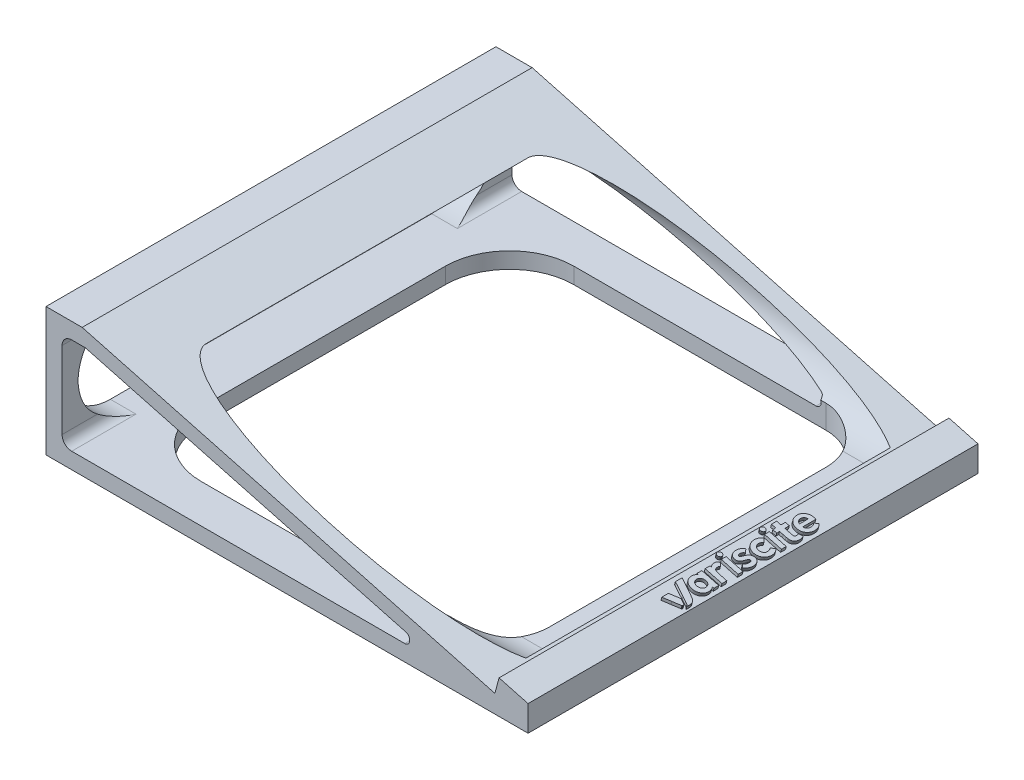
SolidWorks part; units mm, degrees
material "ABS"
ref_plane "Ebene vorne" through (0, 0, 0) normal (1, 0, 0) x (0, 1, 0)
ref_plane "Ebene oben" through (0, 0, 0) normal (0, 0, 1) x (0, 1, 0)
ref_plane "Ebene rechts" through (0, 0, 0) normal (0, 1, 0) x (-1, 0, 0)
sketch "Basis" plane through (0, 0, 0) normal (0, 0, 1) x (0, 1, 0)
  line L0 (0, 0) -> (0, 150)
  line L1 (0, 0) -> (8, 0)
  line L2 (8, 0) -> (10.4201, 9.032)
  line L3 (0, 150) -> (40, 150)
  line L4 (40, 150) -> (40, 138.7441)
  line L5 (40, 138.7441) -> (5.5905, 10.3261)
  line L6 (5.5905, 10.3261) -> (10.4201, 9.032)
  dimension "D1" = 15
  dimension "D2" = 90
  dimension "D3" = 8
  dimension "D4" = 150
  dimension "D5" = 15
  dimension "D6" = 40
  dimension "D8" = 5
extrude "Aufsatz-Linear austragen1" add sketch "Basis" along normal blind 140
sketch "Schnitt Boden" plane through (0.3591, 0, 0) normal (0, 1, 0) x (-1, 0, 0)
  line L0 (139.1032, 140) -> (139.1032, 0) construction
  line L4 (35.6851, 128) -> (114.1032, 128)
  line L6 (20.6851, 113) -> (20.6851, 27)
  line L7 (35.6851, 12) -> (114.1032, 12)
  line L8 (134.1032, 108) -> (134.1032, 32)
  line L9 (10.6851, 140) -> (139.1032, 140) construction
  line L10 (10.6851, 0) -> (139.1032, 0) construction
  line L11 (10.6851, 140) -> (10.6851, 0) construction
  arc A2 (35.6851, 128) -> (20.6851, 113) centre (35.6851, 113) ccw
  arc A3 (20.6851, 27) -> (35.6851, 12) centre (35.6851, 27) ccw
  arc A4 (134.1032, 32) -> (114.1032, 12) centre (114.1032, 32) cw
  arc A5 (134.1032, 108) -> (114.1032, 128) centre (114.1032, 108) ccw
  point P20 (10.6851, 70)
  dimension "D1" = 15
  dimension "D3" = 12
  dimension "D6" = 20
  dimension "D2" = 5
  dimension "D4" = 12
  dimension "D5" = 10
sketch "Schnitt Hinten" plane through (-150, 0, 0) normal (-1, 0, 0) x (0, -1, 0)
  line L0 (-20, 120) -> (-20, 20) construction
  line L1 (-5, 120) -> (-5, 20)
  line L2 (-35, 120) -> (-35, 20)
  line L3 (-40, 0) -> (0, 0) construction
  line L4 (0, 140) -> (0, 0) construction
  arc A0 (-5, 120) -> (-35, 120) centre (-20, 120) ccw
  arc A1 (-35, 20) -> (-5, 20) centre (-20, 20) ccw
  point P2 (-20, 70)
  dimension "D1" = 70
  dimension "D2" = 20
extrude "Schnitt Hinten austragen" cut sketch "Schnitt Hinten" against normal blind 136
extrude "Schnitt Boden austragen" cut sketch "Schnitt Boden" along normal blind 10
sketch "Schnitt Seite" plane through (0, 0, 140) normal (0, 0, 1) x (1, 0, 0)
  line L0 (-142, 35) -> (-137.7635, 35)
  line L1 (-137.7635, 35) -> (-37.9725, 8.2611)
  line L2 (-36.8607, 6.8122) -> (-36.8607, 6.5)
  line L3 (-38.3607, 5) -> (-142, 5)
  line L4 (-145, 8) -> (-145, 32)
  line L5 (-150, 40) -> (-150, 0) construction
  line L6 (-150, 0) -> (0, 0) construction
  line L7 (-10.3261, 5.5905) -> (-138.7441, 40) construction
  arc A0 (-145, 32) -> (-142, 35) centre (-142, 32) cw
  arc A1 (-142, 5) -> (-145, 8) centre (-142, 8) cw
  arc A2 (-38.3607, 5) -> (-36.8607, 6.5) centre (-38.3607, 6.5) ccw
  arc A3 (-36.8607, 6.8122) -> (-37.9725, 8.2611) centre (-38.3607, 6.8122) ccw
  dimension "D5" = 3
  dimension "D6" = 3
  dimension "D7" = 1.5
  dimension "D1" = 5
  dimension "D2" = 5
  dimension "D3" = 0
  dimension "D4" = 5
extrude "Schnitt Seite austragen" cut sketch "Schnitt Seite" against normal blind 140
sketch "Skizze Logo" plane through (2, 7.4641, 0) normal (0.2588, 0.9659, 0) x (-0.9659, 0.2588, 0)
  line L0 (8.7653, 83.336) -> (8.7223, 83.5503)
  line L1 (8.7223, 83.5503) -> (8.6617, 83.7574)
  line L2 (8.6617, 83.7574) -> (8.5841, 83.9565)
  line L3 (8.5841, 83.9565) -> (8.4904, 84.1471)
  line L4 (8.4904, 84.1471) -> (8.3812, 84.3284)
  line L5 (8.3812, 84.3284) -> (8.2572, 84.4998)
  line L6 (8.2572, 84.4998) -> (8.1193, 84.6607)
  line L7 (8.1193, 84.6607) -> (7.968, 84.8103)
  line L8 (7.968, 84.8103) -> (7.8042, 84.948)
  line L9 (7.8042, 84.948) -> (7.6286, 85.0731)
  line L10 (7.6286, 85.0731) -> (7.4418, 85.1851)
  line L11 (7.4418, 85.1851) -> (7.2447, 85.2831)
  line L12 (7.2447, 85.2831) -> (7.0379, 85.3666)
  line L13 (7.0379, 85.3666) -> (6.8221, 85.4349)
  line L14 (6.8221, 85.4349) -> (6.5982, 85.4873)
  line L15 (6.5982, 85.4873) -> (6.3668, 85.5232)
  line L16 (6.3668, 85.5232) -> (6.1055, 85.5395)
  line L17 (6.1055, 85.5395) -> (5.8095, 85.5358)
  line L18 (5.8095, 85.5358) -> (5.5207, 85.5139)
  line L19 (5.5207, 85.5139) -> (5.2806, 85.4757)
  line L20 (5.2806, 85.4757) -> (5.0781, 85.4227)
  line L21 (5.0781, 85.4227) -> (4.8833, 85.3574)
  line L22 (4.8833, 85.3574) -> (4.6967, 85.2803)
  line L23 (4.6967, 85.2803) -> (4.5186, 85.1917)
  line L24 (4.5186, 85.1917) -> (4.3495, 85.0921)
  line L25 (4.3495, 85.0921) -> (4.1898, 84.9818)
  line L26 (4.1898, 84.9818) -> (4.0398, 84.8613)
  line L27 (4.0398, 84.8613) -> (3.9, 84.731)
  line L28 (3.9, 84.731) -> (3.7708, 84.5913)
  line L29 (3.7708, 84.5913) -> (3.6526, 84.4425)
  line L30 (3.6526, 84.4425) -> (3.5458, 84.2852)
  line L31 (3.5458, 84.2852) -> (3.4507, 84.1196)
  line L32 (3.4507, 84.1196) -> (3.3679, 83.9462)
  line L33 (3.3679, 83.9462) -> (3.2976, 83.7654)
  line L34 (3.2976, 83.7654) -> (3.2404, 83.5777)
  line L35 (3.2404, 83.5777) -> (3.1965, 83.3833)
  line L36 (3.1965, 83.3833) -> (3.1685, 83.1466)
  line L37 (3.1685, 83.1466) -> (3.1596, 82.8688)
  line L38 (3.1596, 82.8688) -> (3.1699, 82.5946)
  line L39 (3.1699, 82.5946) -> (3.1992, 82.3684)
  line L40 (3.1992, 82.3684) -> (3.274, 82.0965)
  line L41 (3.274, 82.0965) -> (3.3828, 81.8376)
  line L42 (3.3828, 81.8376) -> (3.5252, 81.5928)
  line L43 (3.5252, 81.5928) -> (3.7004, 81.3632)
  line L44 (3.7004, 81.3632) -> (3.7878, 81.262)
  line L45 (3.7878, 81.262) -> (3.523, 81.262)
  line L46 (3.523, 81.262) -> (3.2582, 81.262)
  line L47 (3.2582, 81.262) -> (3.2582, 80.5244)
  line L48 (3.2582, 80.5244) -> (3.2582, 79.7869)
  line L49 (3.2582, 79.7869) -> (5.9706, 79.7869)
  line L50 (5.9706, 79.7869) -> (8.6831, 79.7869)
  line L51 (8.6831, 79.7869) -> (8.6831, 80.5244)
  line L52 (8.6831, 80.5244) -> (8.6831, 81.262)
  line L53 (8.6831, 81.262) -> (8.4181, 81.262)
  line L54 (8.4181, 81.262) -> (8.1531, 81.262)
  line L55 (8.1531, 81.262) -> (8.2585, 81.3751)
  line L56 (8.2585, 81.3751) -> (8.4117, 81.5635)
  line L57 (8.4117, 81.5635) -> (8.5405, 81.7728)
  line L58 (8.5405, 81.7728) -> (8.6441, 82.0005)
  line L59 (8.6441, 82.0005) -> (8.7221, 82.2444)
  line L60 (8.7221, 82.2444) -> (8.7738, 82.5022)
  line L61 (8.7738, 82.5022) -> (8.7986, 82.7716)
  line L62 (8.7986, 82.7716) -> (8.796, 83.0503)
  line L63 (8.796, 83.0503) -> (8.7653, 83.336)
  line L64 (7.4097, 82.2247) -> (7.3649, 82.0826)
  line L65 (7.3649, 82.0826) -> (7.3051, 81.9471)
  line L66 (7.3051, 81.9471) -> (7.2312, 81.8194)
  line L67 (7.2312, 81.8194) -> (7.1442, 81.7007)
  line L68 (7.1442, 81.7007) -> (7.0451, 81.5922)
  line L69 (7.0451, 81.5922) -> (6.9348, 81.495)
  line L70 (6.9348, 81.495) -> (6.8142, 81.4103)
  line L71 (6.8142, 81.4103) -> (6.6844, 81.3393)
  line L72 (6.6844, 81.3393) -> (6.5039, 81.2616)
  line L73 (6.5039, 81.2616) -> (6.342, 81.2133)
  line L74 (6.342, 81.2133) -> (6.1728, 81.1888)
  line L75 (6.1728, 81.1888) -> (5.9706, 81.1825)
  line L76 (5.9706, 81.1825) -> (5.8016, 81.1888)
  line L77 (5.8016, 81.1888) -> (5.6459, 81.2066)
  line L78 (5.6459, 81.2066) -> (5.5019, 81.2367)
  line L79 (5.5019, 81.2367) -> (5.3678, 81.2798)
  line L80 (5.3678, 81.2798) -> (5.2421, 81.3364)
  line L81 (5.2421, 81.3364) -> (5.123, 81.4072)
  line L82 (5.123, 81.4072) -> (5.0087, 81.493)
  line L83 (5.0087, 81.493) -> (4.8977, 81.5942)
  line L84 (4.8977, 81.5942) -> (4.8015, 81.6985)
  line L85 (4.8015, 81.6985) -> (4.7191, 81.8071)
  line L86 (4.7191, 81.8071) -> (4.65, 81.9208)
  line L87 (4.65, 81.9208) -> (4.594, 82.0402)
  line L88 (4.594, 82.0402) -> (4.5509, 82.1661)
  line L89 (4.5509, 82.1661) -> (4.5204, 82.2992)
  line L90 (4.5204, 82.2992) -> (4.5021, 82.4401)
  line L91 (4.5021, 82.4401) -> (4.4959, 82.5895)
  line L92 (4.4959, 82.5895) -> (4.5046, 82.7693)
  line L93 (4.5046, 82.7693) -> (4.5314, 82.9407)
  line L94 (4.5314, 82.9407) -> (4.5759, 83.103)
  line L95 (4.5759, 83.103) -> (4.6376, 83.2551)
  line L96 (4.6376, 83.2551) -> (4.716, 83.3962)
  line L97 (4.716, 83.3962) -> (4.8109, 83.5254)
  line L98 (4.8109, 83.5254) -> (4.9216, 83.6418)
  line L99 (4.9216, 83.6418) -> (5.0478, 83.7444)
  line L100 (5.0478, 83.7444) -> (5.1467, 83.8087)
  line L101 (5.1467, 83.8087) -> (5.2515, 83.8648)
  line L102 (5.2515, 83.8648) -> (5.4773, 83.9516)
  line L103 (5.4773, 83.9516) -> (5.7229, 84.0043)
  line L104 (5.7229, 84.0043) -> (5.9856, 84.022)
  line L105 (5.9856, 84.022) -> (6.2383, 84.0043)
  line L106 (6.2383, 84.0043) -> (6.474, 83.9522)
  line L107 (6.474, 83.9522) -> (6.6904, 83.8674)
  line L108 (6.6904, 83.8674) -> (6.885, 83.7516)
  line L109 (6.885, 83.7516) -> (7.0557, 83.6063)
  line L110 (7.0557, 83.6063) -> (7.2001, 83.4334)
  line L111 (7.2001, 83.4334) -> (7.3159, 83.2343)
  line L112 (7.3159, 83.2343) -> (7.4008, 83.0108)
  line L113 (7.4008, 83.0108) -> (7.4319, 82.8374)
  line L114 (7.4319, 82.8374) -> (7.4441, 82.6215)
  line L115 (7.4441, 82.6215) -> (7.4368, 82.4037)
  line L116 (7.4368, 82.4037) -> (7.4097, 82.2247)
  line L117 (8.7651, 50.6421) -> (8.7206, 50.846)
  line L118 (8.7206, 50.846) -> (8.6623, 51.0448)
  line L119 (8.6623, 51.0448) -> (8.5907, 51.238)
  line L120 (8.5907, 51.238) -> (8.5066, 51.4248)
  line L121 (8.5066, 51.4248) -> (8.4104, 51.6046)
  line L122 (8.4104, 51.6046) -> (8.3029, 51.7765)
  line L123 (8.3029, 51.7765) -> (8.1846, 51.94)
  line L124 (8.1846, 51.94) -> (8.0562, 52.0943)
  line L125 (8.0562, 52.0943) -> (7.9183, 52.2387)
  line L126 (7.9183, 52.2387) -> (7.7716, 52.3726)
  line L127 (7.7716, 52.3726) -> (7.6166, 52.4951)
  line L128 (7.6166, 52.4951) -> (7.4541, 52.6057)
  line L129 (7.4541, 52.6057) -> (7.2845, 52.7036)
  line L130 (7.2845, 52.7036) -> (7.1086, 52.7881)
  line L131 (7.1086, 52.7881) -> (6.9269, 52.8585)
  line L132 (6.9269, 52.8585) -> (6.7401, 52.9141)
  line L133 (6.7401, 52.9141) -> (6.4354, 52.975)
  line L134 (6.4354, 52.975) -> (6.1284, 53.0047)
  line L135 (6.1284, 53.0047) -> (5.8223, 53.0036)
  line L136 (5.8223, 53.0036) -> (5.5208, 52.9725)
  line L137 (5.5208, 52.9725) -> (5.2272, 52.9116)
  line L138 (5.2272, 52.9116) -> (4.9449, 52.8217)
  line L139 (4.9449, 52.8217) -> (4.6774, 52.7032)
  line L140 (4.6774, 52.7032) -> (4.428, 52.5566)
  line L141 (4.428, 52.5566) -> (4.1935, 52.3806)
  line L142 (4.1935, 52.3806) -> (3.9807, 52.1824)
  line L143 (3.9807, 52.1824) -> (3.7902, 51.9629)
  line L144 (3.7902, 51.9629) -> (3.6227, 51.7231)
  line L145 (3.6227, 51.7231) -> (3.4787, 51.464)
  line L146 (3.4787, 51.464) -> (3.359, 51.1866)
  line L147 (3.359, 51.1866) -> (3.264, 50.8919)
  line L148 (3.264, 50.8919) -> (3.1944, 50.5808)
  line L149 (3.1944, 50.5808) -> (3.1649, 50.3128)
  line L150 (3.1649, 50.3128) -> (3.1558, 49.9902)
  line L151 (3.1558, 49.9902) -> (3.1668, 49.6655)
  line L152 (3.1668, 49.6655) -> (3.1978, 49.3911)
  line L153 (3.1978, 49.3911) -> (3.244, 49.1706)
  line L154 (3.244, 49.1706) -> (3.3031, 48.959)
  line L155 (3.3031, 48.959) -> (3.3748, 48.7571)
  line L156 (3.3748, 48.7571) -> (3.4588, 48.5654)
  line L157 (3.4588, 48.5654) -> (3.5549, 48.3844)
  line L158 (3.5549, 48.3844) -> (3.6626, 48.2148)
  line L159 (3.6626, 48.2148) -> (3.7818, 48.0572)
  line L160 (3.7818, 48.0572) -> (3.9121, 47.9122)
  line L161 (3.9121, 47.9122) -> (4.0791, 47.7418)
  line L162 (4.0791, 47.7418) -> (4.504, 48.1792)
  line L163 (4.504, 48.1792) -> (4.9289, 48.6165)
  line L164 (4.9289, 48.6165) -> (4.7974, 48.7619)
  line L165 (4.7974, 48.7619) -> (4.7038, 48.8749)
  line L166 (4.7038, 48.8749) -> (4.6229, 48.9934)
  line L167 (4.6229, 48.9934) -> (4.5544, 49.1186)
  line L168 (4.5544, 49.1186) -> (4.4979, 49.2514)
  line L169 (4.4979, 49.2514) -> (4.4529, 49.3929)
  line L170 (4.4529, 49.3929) -> (4.419, 49.5442)
  line L171 (4.419, 49.5442) -> (4.3959, 49.7065)
  line L172 (4.3959, 49.7065) -> (4.3832, 49.8806)
  line L173 (4.3832, 49.8806) -> (4.3808, 50.054)
  line L174 (4.3808, 50.054) -> (4.389, 50.2147)
  line L175 (4.389, 50.2147) -> (4.4085, 50.3645)
  line L176 (4.4085, 50.3645) -> (4.4395, 50.505)
  line L177 (4.4395, 50.505) -> (4.4825, 50.6377)
  line L178 (4.4825, 50.6377) -> (4.5381, 50.7643)
  line L179 (4.5381, 50.7643) -> (4.6065, 50.8864)
  line L180 (4.6065, 50.8864) -> (4.6883, 51.0056)
  line L181 (4.6883, 51.0056) -> (4.8341, 51.1662)
  line L182 (4.8341, 51.1662) -> (5.0108, 51.3051)
  line L183 (5.0108, 51.3051) -> (5.2067, 51.4145)
  line L184 (5.2067, 51.4145) -> (5.4104, 51.4868)
  line L185 (5.4104, 51.4868) -> (5.4707, 51.5019)
  line L186 (5.4707, 51.5019) -> (5.4768, 49.4602)
  line L187 (5.4768, 49.4602) -> (5.4829, 47.4184)
  line L188 (5.4829, 47.4184) -> (5.5781, 47.3951)
  line L189 (5.5781, 47.3951) -> (5.7816, 47.3785)
  line L190 (5.7816, 47.3785) -> (6.1372, 47.3713)
  line L191 (6.1372, 47.3713) -> (6.5653, 47.3805)
  line L192 (6.5653, 47.3805) -> (6.6938, 47.3993)
  line L193 (6.6938, 47.3993) -> (6.8321, 47.4336)
  line L194 (6.8321, 47.4336) -> (7.0177, 47.4911)
  line L195 (7.0177, 47.4911) -> (7.1969, 47.561)
  line L196 (7.1969, 47.561) -> (7.3691, 47.6425)
  line L197 (7.3691, 47.6425) -> (7.534, 47.7353)
  line L198 (7.534, 47.7353) -> (7.691, 47.8389)
  line L199 (7.691, 47.8389) -> (7.8398, 47.9526)
  line L200 (7.8398, 47.9526) -> (7.9797, 48.0761)
  line L201 (7.9797, 48.0761) -> (8.1104, 48.2088)
  line L202 (8.1104, 48.2088) -> (8.2314, 48.3501)
  line L203 (8.2314, 48.3501) -> (8.3422, 48.4997)
  line L204 (8.3422, 48.4997) -> (8.4423, 48.6569)
  line L205 (8.4423, 48.6569) -> (8.5313, 48.8212)
  line L206 (8.5313, 48.8212) -> (8.6087, 48.9922)
  line L207 (8.6087, 48.9922) -> (8.6741, 49.1694)
  line L208 (8.6741, 49.1694) -> (8.7269, 49.3522)
  line L209 (8.7269, 49.3522) -> (8.7667, 49.5401)
  line L210 (8.7667, 49.5401) -> (8.7914, 49.7841)
  line L211 (8.7914, 49.7841) -> (8.7992, 50.0931)
  line L212 (8.7992, 50.0931) -> (8.7905, 50.4011)
  line L213 (8.7905, 50.4011) -> (8.7651, 50.6421)
  line L214 (7.5605, 49.7242) -> (7.5279, 49.6062)
  line L215 (7.5279, 49.6062) -> (7.4806, 49.4899)
  line L216 (7.4806, 49.4899) -> (7.4203, 49.3775)
  line L217 (7.4203, 49.3775) -> (7.3484, 49.2709)
  line L218 (7.3484, 49.2709) -> (7.2666, 49.1723)
  line L219 (7.2666, 49.1723) -> (7.1762, 49.0836)
  line L220 (7.1762, 49.0836) -> (7.0789, 49.007)
  line L221 (7.0789, 49.007) -> (6.9762, 48.9445)
  line L222 (6.9762, 48.9445) -> (6.842, 48.8814)
  line L223 (6.842, 48.8814) -> (6.7109, 48.8312)
  line L224 (6.7109, 48.8312) -> (6.6073, 48.802)
  line L225 (6.6073, 48.802) -> (6.5556, 48.8022)
  line L226 (6.5556, 48.8022) -> (6.5458, 49.2065)
  line L227 (6.5458, 49.2065) -> (6.5417, 50.1591)
  line L228 (6.5417, 50.1591) -> (6.5417, 51.502)
  line L229 (6.5417, 51.502) -> (6.6071, 51.4868)
  line L230 (6.6071, 51.4868) -> (6.8473, 51.3866)
  line L231 (6.8473, 51.3866) -> (6.9594, 51.3231)
  line L232 (6.9594, 51.3231) -> (7.0677, 51.2442)
  line L233 (7.0677, 51.2442) -> (7.1704, 51.1523)
  line L234 (7.1704, 51.1523) -> (7.2655, 51.0494)
  line L235 (7.2655, 51.0494) -> (7.3512, 50.9379)
  line L236 (7.3512, 50.9379) -> (7.4256, 50.82)
  line L237 (7.4256, 50.82) -> (7.4868, 50.6979)
  line L238 (7.4868, 50.6979) -> (7.5329, 50.5737)
  line L239 (7.5329, 50.5737) -> (7.5749, 50.3799)
  line L240 (7.5749, 50.3799) -> (7.5939, 50.1601)
  line L241 (7.5939, 50.1601) -> (7.5893, 49.9347)
  line L242 (7.5893, 49.9347) -> (7.5605, 49.7242)
  line L243 (8.7997, 69.5331) -> (8.7498, 69.7927)
  line L244 (8.7498, 69.7927) -> (8.6698, 70.0532)
  line L245 (8.6698, 70.0532) -> (8.5655, 70.2983)
  line L246 (8.5655, 70.2983) -> (8.4429, 70.5117)
  line L247 (8.4429, 70.5117) -> (8.3209, 70.6724)
  line L248 (8.3209, 70.6724) -> (8.1863, 70.8116)
  line L249 (8.1863, 70.8116) -> (8.0391, 70.9293)
  line L250 (8.0391, 70.9293) -> (7.8792, 71.0256)
  line L251 (7.8792, 71.0256) -> (7.7067, 71.1005)
  line L252 (7.7067, 71.1005) -> (7.5215, 71.154)
  line L253 (7.5215, 71.154) -> (7.3235, 71.186)
  line L254 (7.3235, 71.186) -> (7.1127, 71.1967)
  line L255 (7.1127, 71.1967) -> (6.8511, 71.1816)
  line L256 (6.8511, 71.1816) -> (6.6177, 71.1347)
  line L257 (6.6177, 71.1347) -> (6.5106, 71.0986)
  line L258 (6.5106, 71.0986) -> (6.4095, 71.0537)
  line L259 (6.4095, 71.0537) -> (6.314, 70.9996)
  line L260 (6.314, 70.9996) -> (6.2236, 70.9362)
  line L261 (6.2236, 70.9362) -> (6.138, 70.8631)
  line L262 (6.138, 70.8631) -> (6.0569, 70.78)
  line L263 (6.0569, 70.78) -> (5.9064, 70.5827)
  line L264 (5.9064, 70.5827) -> (5.7692, 70.3419)
  line L265 (5.7692, 70.3419) -> (5.6422, 70.0555)
  line L266 (5.6422, 70.0555) -> (5.5523, 69.7862)
  line L267 (5.5523, 69.7862) -> (5.4353, 69.3893)
  line L268 (5.4353, 69.3893) -> (5.2987, 68.9414)
  line L269 (5.2987, 68.9414) -> (5.2374, 68.78)
  line L270 (5.2374, 68.78) -> (5.1774, 68.6541)
  line L271 (5.1774, 68.6541) -> (5.1161, 68.5592)
  line L272 (5.1161, 68.5592) -> (5.0509, 68.4905)
  line L273 (5.0509, 68.4905) -> (4.9794, 68.4435)
  line L274 (4.9794, 68.4435) -> (4.8989, 68.4135)
  line L275 (4.8989, 68.4135) -> (4.822, 68.4009)
  line L276 (4.822, 68.4009) -> (4.7487, 68.4048)
  line L277 (4.7487, 68.4048) -> (4.6797, 68.4247)
  line L278 (4.6797, 68.4247) -> (4.616, 68.4599)
  line L279 (4.616, 68.4599) -> (4.5584, 68.5098)
  line L280 (4.5584, 68.5098) -> (4.508, 68.5737)
  line L281 (4.508, 68.5737) -> (4.4656, 68.651)
  line L282 (4.4656, 68.651) -> (4.432, 68.741)
  line L283 (4.432, 68.741) -> (4.4007, 68.9161)
  line L284 (4.4007, 68.9161) -> (4.3934, 69.187)
  line L285 (4.3934, 69.187) -> (4.4016, 69.3806)
  line L286 (4.4016, 69.3806) -> (4.4235, 69.5645)
  line L287 (4.4235, 69.5645) -> (4.4593, 69.7395)
  line L288 (4.4593, 69.7395) -> (4.5093, 69.9064)
  line L289 (4.5093, 69.9064) -> (4.5738, 70.0658)
  line L290 (4.5738, 70.0658) -> (4.653, 70.2185)
  line L291 (4.653, 70.2185) -> (4.7472, 70.3653)
  line L292 (4.7472, 70.3653) -> (4.8565, 70.5067)
  line L293 (4.8565, 70.5067) -> (5.0016, 70.679)
  line L294 (5.0016, 70.679) -> (4.5641, 71.1183)
  line L295 (4.5641, 71.1183) -> (4.1267, 71.5576)
  line L296 (4.1267, 71.5576) -> (3.9482, 71.3677)
  line L297 (3.9482, 71.3677) -> (3.8246, 71.2252)
  line L298 (3.8246, 71.2252) -> (3.7103, 71.0711)
  line L299 (3.7103, 71.0711) -> (3.6057, 70.9066)
  line L300 (3.6057, 70.9066) -> (3.511, 70.7327)
  line L301 (3.511, 70.7327) -> (3.4264, 70.5504)
  line L302 (3.4264, 70.5504) -> (3.3522, 70.361)
  line L303 (3.3522, 70.361) -> (3.2887, 70.1654)
  line L304 (3.2887, 70.1654) -> (3.236, 69.9648)
  line L305 (3.236, 69.9648) -> (3.1945, 69.7602)
  line L306 (3.1945, 69.7602) -> (3.1644, 69.5527)
  line L307 (3.1644, 69.5527) -> (3.1459, 69.3433)
  line L308 (3.1459, 69.3433) -> (3.1393, 69.1332)
  line L309 (3.1393, 69.1332) -> (3.1449, 68.9234)
  line L310 (3.1449, 68.9234) -> (3.1628, 68.715)
  line L311 (3.1628, 68.715) -> (3.1934, 68.509)
  line L312 (3.1934, 68.509) -> (3.2369, 68.3067)
  line L313 (3.2369, 68.3067) -> (3.3056, 68.0998)
  line L314 (3.3056, 68.0998) -> (3.404, 67.8696)
  line L315 (3.404, 67.8696) -> (3.4727, 67.7355)
  line L316 (3.4727, 67.7355) -> (3.5372, 67.6323)
  line L317 (3.5372, 67.6323) -> (3.6137, 67.5373)
  line L318 (3.6137, 67.5373) -> (3.7181, 67.4281)
  line L319 (3.7181, 67.4281) -> (3.8322, 67.3215)
  line L320 (3.8322, 67.3215) -> (3.9463, 67.2311)
  line L321 (3.9463, 67.2311) -> (4.063, 67.1559)
  line L322 (4.063, 67.1559) -> (4.1846, 67.0949)
  line L323 (4.1846, 67.0949) -> (4.3136, 67.0469)
  line L324 (4.3136, 67.0469) -> (4.4524, 67.0109)
  line L325 (4.4524, 67.0109) -> (4.6036, 66.9857)
  line L326 (4.6036, 66.9857) -> (4.7695, 66.9705)
  line L327 (4.7695, 66.9705) -> (5.0164, 66.9704)
  line L328 (5.0164, 66.9704) -> (5.2457, 67.0016)
  line L329 (5.2457, 67.0016) -> (5.4578, 67.0644)
  line L330 (5.4578, 67.0644) -> (5.6531, 67.1589)
  line L331 (5.6531, 67.1589) -> (5.8318, 67.2853)
  line L332 (5.8318, 67.2853) -> (5.9942, 67.4438)
  line L333 (5.9942, 67.4438) -> (6.1408, 67.6347)
  line L334 (6.1408, 67.6347) -> (6.2718, 67.858)
  line L335 (6.2718, 67.858) -> (6.3552, 68.0473)
  line L336 (6.3552, 68.0473) -> (6.4509, 68.3117)
  line L337 (6.4509, 68.3117) -> (6.5544, 68.6381)
  line L338 (6.5544, 68.6381) -> (6.6613, 69.0132)
  line L339 (6.6613, 69.0132) -> (6.7369, 69.255)
  line L340 (6.7369, 69.255) -> (6.8201, 69.4547)
  line L341 (6.8201, 69.4547) -> (6.9063, 69.6034)
  line L342 (6.9063, 69.6034) -> (6.9493, 69.6558)
  line L343 (6.9493, 69.6558) -> (6.9913, 69.692)
  line L344 (6.9913, 69.692) -> (7.0865, 69.7354)
  line L345 (7.0865, 69.7354) -> (7.1893, 69.7483)
  line L346 (7.1893, 69.7483) -> (7.2887, 69.731)
  line L347 (7.2887, 69.731) -> (7.3737, 69.6837)
  line L348 (7.3737, 69.6837) -> (7.4322, 69.6224)
  line L349 (7.4322, 69.6224) -> (7.4815, 69.5454)
  line L350 (7.4815, 69.5454) -> (7.5214, 69.4543)
  line L351 (7.5214, 69.4543) -> (7.5515, 69.3506)
  line L352 (7.5515, 69.3506) -> (7.5714, 69.2356)
  line L353 (7.5714, 69.2356) -> (7.5809, 69.1109)
  line L354 (7.5809, 69.1109) -> (7.5795, 68.978)
  line L355 (7.5795, 68.978) -> (7.5669, 68.8384)
  line L356 (7.5669, 68.8384) -> (7.5149, 68.5772)
  line L357 (7.5149, 68.5772) -> (7.476, 68.4556)
  line L358 (7.476, 68.4556) -> (7.4282, 68.3395)
  line L359 (7.4282, 68.3395) -> (7.3713, 68.2284)
  line L360 (7.3713, 68.2284) -> (7.3052, 68.1218)
  line L361 (7.3052, 68.1218) -> (7.144, 67.9204)
  line L362 (7.144, 67.9204) -> (7.0208, 67.7877)
  line L363 (7.0208, 67.7877) -> (7.451, 67.3403)
  line L364 (7.451, 67.3403) -> (7.8812, 66.8928)
  line L365 (7.8812, 66.8928) -> (7.9459, 66.9389)
  line L366 (7.9459, 66.9389) -> (8.0455, 67.0263)
  line L367 (8.0455, 67.0263) -> (8.1679, 67.1568)
  line L368 (8.1679, 67.1568) -> (8.291, 67.3055)
  line L369 (8.291, 67.3055) -> (8.3931, 67.4473)
  line L370 (8.3931, 67.4473) -> (8.5356, 67.7048)
  line L371 (8.5356, 67.7048) -> (8.654, 67.9958)
  line L372 (8.654, 67.9958) -> (8.744, 68.3076)
  line L373 (8.744, 68.3076) -> (8.8011, 68.6273)
  line L374 (8.8011, 68.6273) -> (8.817, 68.8351)
  line L375 (8.817, 68.8351) -> (8.822, 69.0826)
  line L376 (8.822, 69.0826) -> (8.8162, 69.3288)
  line L377 (8.8162, 69.3288) -> (8.7997, 69.5331)
  line L378 (9.3612, 56.8265) -> (8.6831, 56.8265)
  line L379 (8.6831, 56.8265) -> (8.6831, 57.2667)
  line L380 (8.6831, 57.2667) -> (8.6831, 57.7068)
  line L381 (8.6831, 57.7068) -> (8.0525, 57.7068)
  line L382 (8.0525, 57.7068) -> (7.422, 57.7068)
  line L383 (7.422, 57.7068) -> (7.422, 57.2667)
  line L384 (7.422, 57.2667) -> (7.422, 56.8265)
  line L385 (7.422, 56.8265) -> (6.2383, 56.8265)
  line L386 (6.2383, 56.8265) -> (5.3276, 56.8194)
  line L387 (5.3276, 56.8194) -> (4.8003, 56.8023)
  line L388 (4.8003, 56.8023) -> (4.5723, 56.7705)
  line L389 (4.5723, 56.7705) -> (4.3514, 56.7197)
  line L390 (4.3514, 56.7197) -> (4.1451, 56.6521)
  line L391 (4.1451, 56.6521) -> (3.961, 56.5698)
  line L392 (3.961, 56.5698) -> (3.7991, 56.4634)
  line L393 (3.7991, 56.4634) -> (3.6286, 56.3154)
  line L394 (3.6286, 56.3154) -> (3.4728, 56.1485)
  line L395 (3.4728, 56.1485) -> (3.3552, 55.9852)
  line L396 (3.3552, 55.9852) -> (3.2864, 55.8562)
  line L397 (3.2864, 55.8562) -> (3.2267, 55.7182)
  line L398 (3.2267, 55.7182) -> (3.1761, 55.5714)
  line L399 (3.1761, 55.5714) -> (3.1346, 55.4158)
  line L400 (3.1346, 55.4158) -> (3.1023, 55.2517)
  line L401 (3.1023, 55.2517) -> (3.0791, 55.079)
  line L402 (3.0791, 55.079) -> (3.0606, 54.7089)
  line L403 (3.0606, 54.7089) -> (3.0689, 54.4372)
  line L404 (3.0689, 54.4372) -> (3.0949, 54.1968)
  line L405 (3.0949, 54.1968) -> (3.1408, 53.9751)
  line L406 (3.1408, 53.9751) -> (3.2084, 53.7594)
  line L407 (3.2084, 53.7594) -> (3.3235, 53.5045)
  line L408 (3.3235, 53.5045) -> (3.3784, 53.4125)
  line L409 (3.3784, 53.4125) -> (3.4142, 53.3765)
  line L410 (3.4142, 53.3765) -> (3.9195, 53.5656)
  line L411 (3.9195, 53.5656) -> (4.4787, 53.7796)
  line L412 (4.4787, 53.7796) -> (4.5453, 53.8044)
  line L413 (4.5453, 53.8044) -> (4.4865, 53.9057)
  line L414 (4.4865, 53.9057) -> (4.4223, 54.0385)
  line L415 (4.4223, 54.0385) -> (4.3799, 54.1794)
  line L416 (4.3799, 54.1794) -> (4.3585, 54.3331)
  line L417 (4.3585, 54.3331) -> (4.357, 54.5041)
  line L418 (4.357, 54.5041) -> (4.3777, 54.7052)
  line L419 (4.3777, 54.7052) -> (4.4005, 54.7764)
  line L420 (4.4005, 54.7764) -> (4.437, 54.8517)
  line L421 (4.437, 54.8517) -> (4.5121, 54.9599)
  line L422 (4.5121, 54.9599) -> (4.6093, 55.0492)
  line L423 (4.6093, 55.0492) -> (4.7243, 55.1166)
  line L424 (4.7243, 55.1166) -> (4.8531, 55.1589)
  line L425 (4.8531, 55.1589) -> (5.258, 55.1781)
  line L426 (5.258, 55.1781) -> (6.1978, 55.1848)
  line L427 (6.1978, 55.1848) -> (7.422, 55.1848)
  line L428 (7.422, 55.1848) -> (7.422, 54.4829)
  line L429 (7.422, 54.4829) -> (7.422, 53.781)
  line L430 (7.422, 53.781) -> (8.0525, 53.781)
  line L431 (8.0525, 53.781) -> (8.6831, 53.781)
  line L432 (8.6831, 53.781) -> (8.6831, 54.4829)
  line L433 (8.6831, 54.4829) -> (8.6831, 55.1848)
  line L434 (8.6831, 55.1848) -> (9.3612, 55.1848)
  line L435 (9.3612, 55.1848) -> (10.0393, 55.1848)
  line L436 (10.0393, 55.1848) -> (10.0393, 56.0056)
  line L437 (10.0393, 56.0056) -> (10.0393, 56.8265)
  line L438 (10.0393, 56.8265) -> (9.3612, 56.8265)
  line L439 (8.8011, 63.6787) -> (8.771, 63.9006)
  line L440 (8.771, 63.9006) -> (8.7268, 64.1166)
  line L441 (8.7268, 64.1166) -> (8.6691, 64.3261)
  line L442 (8.6691, 64.3261) -> (8.5982, 64.5285)
  line L443 (8.5982, 64.5285) -> (8.5145, 64.7232)
  line L444 (8.5145, 64.7232) -> (8.4185, 64.9098)
  line L445 (8.4185, 64.9098) -> (8.3107, 65.0876)
  line L446 (8.3107, 65.0876) -> (8.1913, 65.2561)
  line L447 (8.1913, 65.2561) -> (8.061, 65.4148)
  line L448 (8.061, 65.4148) -> (7.92, 65.563)
  line L449 (7.92, 65.563) -> (7.7688, 65.7002)
  line L450 (7.7688, 65.7002) -> (7.6079, 65.8259)
  line L451 (7.6079, 65.8259) -> (7.4376, 65.9395)
  line L452 (7.4376, 65.9395) -> (7.2585, 66.0405)
  line L453 (7.2585, 66.0405) -> (7.0708, 66.1282)
  line L454 (7.0708, 66.1282) -> (6.8751, 66.2021)
  line L455 (6.8751, 66.2021) -> (6.6178, 66.2741)
  line L456 (6.6178, 66.2741) -> (6.3532, 66.3208)
  line L457 (6.3532, 66.3208) -> (6.0845, 66.3425)
  line L458 (6.0845, 66.3425) -> (5.8145, 66.3392)
  line L459 (5.8145, 66.3392) -> (5.5465, 66.3113)
  line L460 (5.5465, 66.3113) -> (5.2834, 66.2588)
  line L461 (5.2834, 66.2588) -> (5.0283, 66.1819)
  line L462 (5.0283, 66.1819) -> (4.7843, 66.0808)
  line L463 (4.7843, 66.0808) -> (4.5037, 65.9277)
  line L464 (4.5037, 65.9277) -> (4.2464, 65.7469)
  line L465 (4.2464, 65.7469) -> (4.0133, 65.5397)
  line L466 (4.0133, 65.5397) -> (3.8053, 65.3074)
  line L467 (3.8053, 65.3074) -> (3.6235, 65.051)
  line L468 (3.6235, 65.051) -> (3.4687, 64.7719)
  line L469 (3.4687, 64.7719) -> (3.342, 64.4711)
  line L470 (3.342, 64.4711) -> (3.2442, 64.1499)
  line L471 (3.2442, 64.1499) -> (3.1927, 63.8505)
  line L472 (3.1927, 63.8505) -> (3.1665, 63.4945)
  line L473 (3.1665, 63.4945) -> (3.1675, 63.1342)
  line L474 (3.1675, 63.1342) -> (3.1976, 62.8224)
  line L475 (3.1976, 62.8224) -> (3.2415, 62.6069)
  line L476 (3.2415, 62.6069) -> (3.2999, 62.3981)
  line L477 (3.2999, 62.3981) -> (3.3729, 62.196)
  line L478 (3.3729, 62.196) -> (3.4604, 62.0007)
  line L479 (3.4604, 62.0007) -> (3.5625, 61.8122)
  line L480 (3.5625, 61.8122) -> (3.679, 61.6305)
  line L481 (3.679, 61.6305) -> (3.8101, 61.4557)
  line L482 (3.8101, 61.4557) -> (3.9556, 61.2877)
  line L483 (3.9556, 61.2877) -> (4.066, 61.1687)
  line L484 (4.066, 61.1687) -> (4.5381, 61.6554)
  line L485 (4.5381, 61.6554) -> (5.0101, 62.1422)
  line L486 (5.0101, 62.1422) -> (4.9134, 62.2446)
  line L487 (4.9134, 62.2446) -> (4.8171, 62.3611)
  line L488 (4.8171, 62.3611) -> (4.7266, 62.4978)
  line L489 (4.7266, 62.4978) -> (4.6491, 62.6426)
  line L490 (4.6491, 62.6426) -> (4.5919, 62.7832)
  line L491 (4.5919, 62.7832) -> (4.5581, 62.9073)
  line L492 (4.5581, 62.9073) -> (4.5338, 63.0438)
  line L493 (4.5338, 63.0438) -> (4.514, 63.3367)
  line L494 (4.514, 63.3367) -> (4.5327, 63.6269)
  line L495 (4.5327, 63.6269) -> (4.5565, 63.76)
  line L496 (4.5565, 63.76) -> (4.5899, 63.8792)
  line L497 (4.5899, 63.8792) -> (4.6509, 64.0265)
  line L498 (4.6509, 64.0265) -> (4.7288, 64.1649)
  line L499 (4.7288, 64.1649) -> (4.8224, 64.2933)
  line L500 (4.8224, 64.2933) -> (4.9302, 64.4104)
  line L501 (4.9302, 64.4104) -> (5.0511, 64.5149)
  line L502 (5.0511, 64.5149) -> (5.1837, 64.6056)
  line L503 (5.1837, 64.6056) -> (5.3269, 64.6812)
  line L504 (5.3269, 64.6812) -> (5.4791, 64.7406)
  line L505 (5.4791, 64.7406) -> (5.5893, 64.7729)
  line L506 (5.5893, 64.7729) -> (5.69, 64.7923)
  line L507 (5.69, 64.7923) -> (5.9587, 64.8055)
  line L508 (5.9587, 64.8055) -> (6.1297, 64.8017)
  line L509 (6.1297, 64.8017) -> (6.283, 64.7871)
  line L510 (6.283, 64.7871) -> (6.4217, 64.7605)
  line L511 (6.4217, 64.7605) -> (6.5491, 64.7207)
  line L512 (6.5491, 64.7207) -> (6.6683, 64.6665)
  line L513 (6.6683, 64.6665) -> (6.7824, 64.5966)
  line L514 (6.7824, 64.5966) -> (6.8946, 64.51)
  line L515 (6.8946, 64.51) -> (7.0082, 64.4053)
  line L516 (7.0082, 64.4053) -> (7.1207, 64.2834)
  line L517 (7.1207, 64.2834) -> (7.2155, 64.1575)
  line L518 (7.2155, 64.1575) -> (7.293, 64.0265)
  line L519 (7.293, 64.0265) -> (7.3538, 63.8891)
  line L520 (7.3538, 63.8891) -> (7.3982, 63.744)
  line L521 (7.3982, 63.744) -> (7.4268, 63.5901)
  line L522 (7.4268, 63.5901) -> (7.4399, 63.426)
  line L523 (7.4399, 63.426) -> (7.4381, 63.2506)
  line L524 (7.4381, 63.2506) -> (7.4248, 63.1017)
  line L525 (7.4248, 63.1017) -> (7.4003, 62.957)
  line L526 (7.4003, 62.957) -> (7.3652, 62.8177)
  line L527 (7.3652, 62.8177) -> (7.32, 62.685)
  line L528 (7.32, 62.685) -> (7.265, 62.5602)
  line L529 (7.265, 62.5602) -> (7.2007, 62.4444)
  line L530 (7.2007, 62.4444) -> (7.1278, 62.3389)
  line L531 (7.1278, 62.3389) -> (7.0465, 62.2449)
  line L532 (7.0465, 62.2449) -> (6.9594, 62.1552)
  line L533 (6.9594, 62.1552) -> (7.4346, 61.6787)
  line L534 (7.4346, 61.6787) -> (7.9098, 61.2022)
  line L535 (7.9098, 61.2022) -> (8.0716, 61.371)
  line L536 (8.0716, 61.371) -> (8.2609, 61.5958)
  line L537 (8.2609, 61.5958) -> (8.4247, 61.847)
  line L538 (8.4247, 61.847) -> (8.5619, 62.1204)
  line L539 (8.5619, 62.1204) -> (8.671, 62.4121)
  line L540 (8.671, 62.4121) -> (8.7507, 62.7178)
  line L541 (8.7507, 62.7178) -> (8.7999, 63.0336)
  line L542 (8.7999, 63.0336) -> (8.8171, 63.3552)
  line L543 (8.8171, 63.3552) -> (8.8011, 63.6787)
  line L544 (9.2125, 87.2932) -> (5.409, 88.8313)
  line L545 (5.409, 88.8313) -> (3.9054, 89.4497)
  line L546 (3.9054, 89.4497) -> (3.2244, 89.7399)
  line L547 (3.2244, 89.7399) -> (3.0916, 89.8237)
  line L548 (3.0916, 89.8237) -> (2.9593, 89.9301)
  line L549 (2.9593, 89.9301) -> (2.8417, 90.0466)
  line L550 (2.8417, 90.0466) -> (2.753, 90.1607)
  line L551 (2.753, 90.1607) -> (2.6842, 90.2677)
  line L552 (2.6842, 90.2677) -> (2.693, 89.5777)
  line L553 (2.693, 89.5777) -> (2.7031, 89.1222)
  line L554 (2.7031, 89.1222) -> (2.7284, 88.8359)
  line L555 (2.7284, 88.8359) -> (2.7514, 88.7282)
  line L556 (2.7514, 88.7282) -> (2.7837, 88.629)
  line L557 (2.7837, 88.629) -> (2.8835, 88.4119)
  line L558 (2.8835, 88.4119) -> (2.9533, 88.2854)
  line L559 (2.9533, 88.2854) -> (3.0331, 88.1623)
  line L560 (3.0331, 88.1623) -> (3.2179, 87.9319)
  line L561 (3.2179, 87.9319) -> (3.4281, 87.7313)
  line L562 (3.4281, 87.7313) -> (3.5397, 87.6455)
  line L563 (3.5397, 87.6455) -> (3.654, 87.5712)
  line L564 (3.654, 87.5712) -> (4.6016, 87.1597)
  line L565 (4.6016, 87.1597) -> (6.5785, 86.3226)
  line L566 (6.5785, 86.3226) -> (8.5705, 85.4871)
  line L567 (8.5705, 85.4871) -> (9.5635, 85.0808)
  line L568 (9.5635, 85.0808) -> (9.579, 85.0784)
  line L569 (9.579, 85.0784) -> (9.5907, 85.09)
  line L570 (9.5907, 85.09) -> (9.6049, 85.2013)
  line L571 (9.6049, 85.2013) -> (9.611, 86.0999)
  line L572 (9.611, 86.0999) -> (9.611, 87.134)
  line L573 (9.611, 87.134) -> (9.2125, 87.2932)
  line L574 (8.7647, 76.2456) -> (8.7017, 76.4992)
  line L575 (8.7017, 76.4992) -> (8.6077, 76.7304)
  line L576 (8.6077, 76.7304) -> (8.4812, 76.9421)
  line L577 (8.4812, 76.9421) -> (8.3208, 77.1374)
  line L578 (8.3208, 77.1374) -> (8.2003, 77.2648)
  line L579 (8.2003, 77.2648) -> (8.4417, 77.2648)
  line L580 (8.4417, 77.2648) -> (8.6831, 77.2648)
  line L581 (8.6831, 77.2648) -> (8.6831, 78.0143)
  line L582 (8.6831, 78.0143) -> (8.6831, 78.7638)
  line L583 (8.6831, 78.7638) -> (5.9706, 78.7638)
  line L584 (5.9706, 78.7638) -> (3.2582, 78.7638)
  line L585 (3.2582, 78.7638) -> (3.2582, 78.0143)
  line L586 (3.2582, 78.0143) -> (3.2582, 77.2648)
  line L587 (3.2582, 77.2648) -> (4.8345, 77.2646)
  line L588 (4.8345, 77.2646) -> (6.0223, 77.2579)
  line L589 (6.0223, 77.2579) -> (6.5604, 77.2402)
  line L590 (6.5604, 77.2402) -> (6.7804, 77.188)
  line L591 (6.7804, 77.188) -> (6.9673, 77.107)
  line L592 (6.9673, 77.107) -> (7.0498, 77.0548)
  line L593 (7.0498, 77.0548) -> (7.1259, 76.9944)
  line L594 (7.1259, 76.9944) -> (7.2614, 76.8473)
  line L595 (7.2614, 76.8473) -> (7.3587, 76.7014)
  line L596 (7.3587, 76.7014) -> (7.4182, 76.5572)
  line L597 (7.4182, 76.5572) -> (7.4482, 76.3858)
  line L598 (7.4482, 76.3858) -> (7.4569, 76.1584)
  line L599 (7.4569, 76.1584) -> (7.4557, 75.9842)
  line L600 (7.4557, 75.9842) -> (7.4477, 75.8738)
  line L601 (7.4477, 75.8738) -> (7.4278, 75.7927)
  line L602 (7.4278, 75.7927) -> (7.3909, 75.7063)
  line L603 (7.3909, 75.7063) -> (7.3267, 75.5877)
  line L604 (7.3267, 75.5877) -> (7.2662, 75.5029)
  line L605 (7.2662, 75.5029) -> (7.2081, 75.4423)
  line L606 (7.2081, 75.4423) -> (7.7369, 74.9703)
  line L607 (7.7369, 74.9703) -> (8.2656, 74.4982)
  line L608 (8.2656, 74.4982) -> (8.3732, 74.6186)
  line L609 (8.3732, 74.6186) -> (8.4988, 74.7791)
  line L610 (8.4988, 74.7791) -> (8.6033, 74.9555)
  line L611 (8.6033, 74.9555) -> (8.6864, 75.1459)
  line L612 (8.6864, 75.1459) -> (8.7476, 75.3485)
  line L613 (8.7476, 75.3485) -> (8.7864, 75.5616)
  line L614 (8.7864, 75.5616) -> (8.8025, 75.7833)
  line L615 (8.8025, 75.7833) -> (8.7954, 76.0119)
  line L616 (8.7954, 76.0119) -> (8.7647, 76.2456)
  line L617 (5.9706, 60.2765) -> (3.2582, 60.2765)
  line L618 (3.2582, 60.2765) -> (3.2582, 59.527)
  line L619 (3.2582, 59.527) -> (3.2582, 58.7775)
  line L620 (3.2582, 58.7775) -> (5.9706, 58.7775)
  line L621 (5.9706, 58.7775) -> (8.6831, 58.7775)
  line L622 (8.6831, 58.7775) -> (8.6831, 59.527)
  line L623 (8.6831, 59.527) -> (8.6831, 60.2765)
  line L624 (8.6831, 60.2765) -> (5.9706, 60.2765)
  line L625 (5.9706, 73.7434) -> (3.2582, 73.7434)
  line L626 (3.2582, 73.7434) -> (3.2582, 72.9939)
  line L627 (3.2582, 72.9939) -> (3.2582, 72.2444)
  line L628 (3.2582, 72.2444) -> (5.9706, 72.2444)
  line L629 (5.9706, 72.2444) -> (8.6831, 72.2444)
  line L630 (8.6831, 72.2444) -> (8.6831, 72.9939)
  line L631 (8.6831, 72.9939) -> (8.6831, 73.7434)
  line L632 (8.6831, 73.7434) -> (5.9706, 73.7434)
  line L633 (7.9077, 92.992) -> (5.7038, 92.0112)
  line L634 (5.7038, 92.0112) -> (3.4773, 91.0029)
  line L635 (3.4773, 91.0029) -> (3.418, 90.9512)
  line L636 (3.418, 90.9512) -> (3.3737, 90.8863)
  line L637 (3.3737, 90.8863) -> (3.3449, 90.8121)
  line L638 (3.3449, 90.8121) -> (3.3316, 90.7327)
  line L639 (3.3316, 90.7327) -> (3.3343, 90.6521)
  line L640 (3.3343, 90.6521) -> (3.3531, 90.5741)
  line L641 (3.3531, 90.5741) -> (3.3883, 90.5029)
  line L642 (3.3883, 90.5029) -> (3.4402, 90.4425)
  line L643 (3.4402, 90.4425) -> (3.7195, 90.3049)
  line L644 (3.7195, 90.3049) -> (4.2878, 90.0465)
  line L645 (4.2878, 90.0465) -> (4.8561, 89.7968)
  line L646 (4.8561, 89.7968) -> (5.1352, 89.6848)
  line L647 (5.1352, 89.6848) -> (6.3496, 90.2178)
  line L648 (6.3496, 90.2178) -> (7.835, 90.8895)
  line L649 (7.835, 90.8895) -> (7.9217, 90.9309)
  line L650 (7.9217, 90.9309) -> (7.9217, 91.9615)
  line L651 (7.9217, 91.9615) -> (7.9176, 92.6893)
  line L652 (7.9176, 92.6893) -> (7.9077, 92.992)
  line L653 (10.7528, 73.1404) -> (10.7, 73.3007)
  line L654 (10.7, 73.3007) -> (10.6122, 73.4439)
  line L655 (10.6122, 73.4439) -> (10.492, 73.5667)
  line L656 (10.492, 73.5667) -> (10.3418, 73.6657)
  line L657 (10.3418, 73.6657) -> (10.2702, 73.6996)
  line L658 (10.2702, 73.6996) -> (10.2039, 73.7193)
  line L659 (10.2039, 73.7193) -> (10.0155, 73.7308)
  line L660 (10.0155, 73.7308) -> (9.8272, 73.7194)
  line L661 (9.8272, 73.7194) -> (9.761, 73.6997)
  line L662 (9.761, 73.6997) -> (9.6898, 73.6661)
  line L663 (9.6898, 73.6661) -> (9.5937, 73.6083)
  line L664 (9.5937, 73.6083) -> (9.5098, 73.5422)
  line L665 (9.5098, 73.5422) -> (9.4382, 73.4682)
  line L666 (9.4382, 73.4682) -> (9.3791, 73.3865)
  line L667 (9.3791, 73.3865) -> (9.3328, 73.2976)
  line L668 (9.3328, 73.2976) -> (9.2995, 73.2018)
  line L669 (9.2995, 73.2018) -> (9.2794, 73.0994)
  line L670 (9.2794, 73.0994) -> (9.2726, 72.9907)
  line L671 (9.2726, 72.9907) -> (9.2753, 72.8935)
  line L672 (9.2753, 72.8935) -> (9.2862, 72.8175)
  line L673 (9.2862, 72.8175) -> (9.309, 72.7456)
  line L674 (9.309, 72.7456) -> (9.3476, 72.6606)
  line L675 (9.3476, 72.6606) -> (9.4222, 72.5364)
  line L676 (9.4222, 72.5364) -> (9.5133, 72.434)
  line L677 (9.5133, 72.434) -> (9.6213, 72.3527)
  line L678 (9.6213, 72.3527) -> (9.7468, 72.2922)
  line L679 (9.7468, 72.2922) -> (9.8441, 72.2635)
  line L680 (9.8441, 72.2635) -> (9.9445, 72.2483)
  line L681 (9.9445, 72.2483) -> (10.0462, 72.2464)
  line L682 (10.0462, 72.2464) -> (10.1474, 72.2573)
  line L683 (10.1474, 72.2573) -> (10.2462, 72.2809)
  line L684 (10.2462, 72.2809) -> (10.3408, 72.3168)
  line L685 (10.3408, 72.3168) -> (10.4294, 72.3646)
  line L686 (10.4294, 72.3646) -> (10.5101, 72.4241)
  line L687 (10.5101, 72.4241) -> (10.575, 72.49)
  line L688 (10.575, 72.49) -> (10.632, 72.5684)
  line L689 (10.632, 72.5684) -> (10.6801, 72.6565)
  line L690 (10.6801, 72.6565) -> (10.7183, 72.7514)
  line L691 (10.7183, 72.7514) -> (10.7456, 72.8501)
  line L692 (10.7456, 72.8501) -> (10.7612, 72.9498)
  line L693 (10.7612, 72.9498) -> (10.7639, 73.0475)
  line L694 (10.7639, 73.0475) -> (10.7528, 73.1404)
  line L695 (10.7528, 59.6735) -> (10.6999, 59.834)
  line L696 (10.6999, 59.834) -> (10.612, 59.9773)
  line L697 (10.612, 59.9773) -> (10.4917, 60.0999)
  line L698 (10.4917, 60.0999) -> (10.3418, 60.1982)
  line L699 (10.3418, 60.1982) -> (10.2703, 60.2316)
  line L700 (10.2703, 60.2316) -> (10.2038, 60.2512)
  line L701 (10.2038, 60.2512) -> (10.0155, 60.2627)
  line L702 (10.0155, 60.2627) -> (9.8284, 60.2514)
  line L703 (9.8284, 60.2514) -> (9.7629, 60.2325)
  line L704 (9.7629, 60.2325) -> (9.6943, 60.2006)
  line L705 (9.6943, 60.2006) -> (9.5386, 60.0986)
  line L706 (9.5386, 60.0986) -> (9.4739, 60.0388)
  line L707 (9.4739, 60.0388) -> (9.418, 59.9732)
  line L708 (9.418, 59.9732) -> (9.3708, 59.9017)
  line L709 (9.3708, 59.9017) -> (9.3322, 59.8241)
  line L710 (9.3322, 59.8241) -> (9.2808, 59.6507)
  line L711 (9.2808, 59.6507) -> (9.2685, 59.5323)
  line L712 (9.2685, 59.5323) -> (9.2751, 59.4159)
  line L713 (9.2751, 59.4159) -> (9.2998, 59.3033)
  line L714 (9.2998, 59.3033) -> (9.3415, 59.1963)
  line L715 (9.3415, 59.1963) -> (9.3996, 59.0966)
  line L716 (9.3996, 59.0966) -> (9.4731, 59.0061)
  line L717 (9.4731, 59.0061) -> (9.5611, 58.9265)
  line L718 (9.5611, 58.9265) -> (9.6629, 58.8595)
  line L719 (9.6629, 58.8595) -> (9.7376, 58.8217)
  line L720 (9.7376, 58.8217) -> (9.8052, 58.8005)
  line L721 (9.8052, 58.8005) -> (9.8898, 58.7914)
  line L722 (9.8898, 58.7914) -> (10.0155, 58.7894)
  line L723 (10.0155, 58.7894) -> (10.1412, 58.7914)
  line L724 (10.1412, 58.7914) -> (10.2257, 58.8005)
  line L725 (10.2257, 58.8005) -> (10.2933, 58.8217)
  line L726 (10.2933, 58.8217) -> (10.3681, 58.8595)
  line L727 (10.3681, 58.8595) -> (10.479, 58.9336)
  line L728 (10.479, 58.9336) -> (10.5679, 59.0131)
  line L729 (10.5679, 59.0131) -> (10.6212, 59.0824)
  line L730 (10.6212, 59.0824) -> (10.667, 59.1592)
  line L731 (10.667, 59.1592) -> (10.7336, 59.3281)
  line L732 (10.7336, 59.3281) -> (10.7636, 59.5046)
  line L733 (10.7636, 59.5046) -> (10.7636, 59.591)
  line L734 (10.7636, 59.591) -> (10.7528, 59.6735)
  line L737 (2.0706, 140) -> (11.4211, 140) construction
  line L738 (2.0706, 0) -> (11.4211, 0) construction
extrude "Logo austragen" add sketch "Skizze Logo" along normal blind 1
